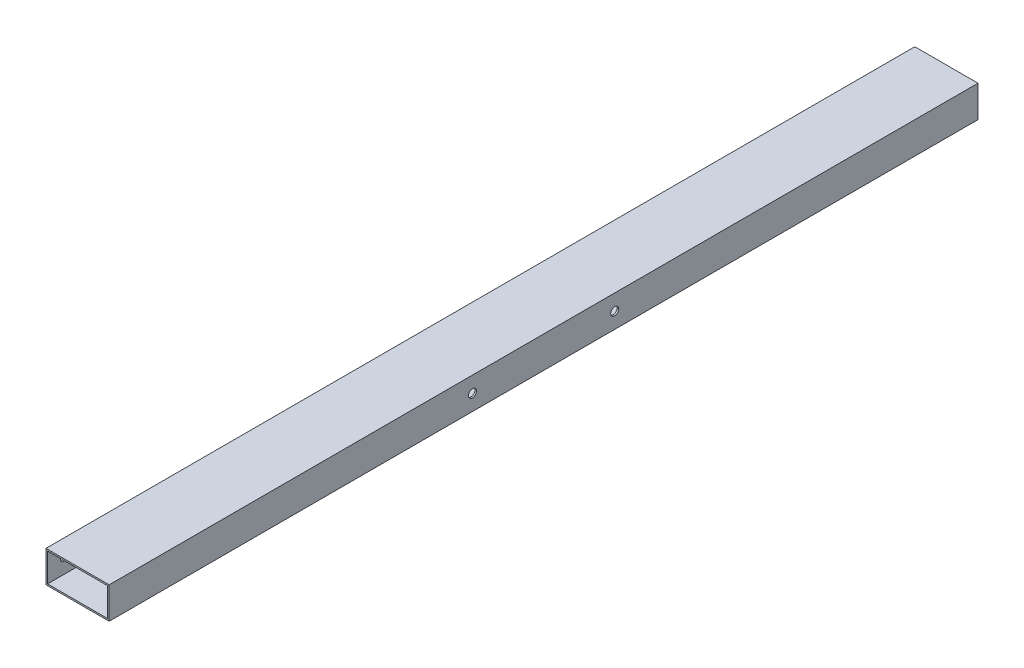
SolidWorks part; units mm, degrees
material "1060 合金"
ref_plane "前视基准面" through (0, 0, 0) normal (0, 0, 1) x (1, 0, 0)
ref_plane "上视基准面" through (0, 0, 0) normal (0, 1, 0) x (1, 0, 0)
ref_plane "右视基准面" through (0, 0, 0) normal (1, 0, 0) x (0, 0, -1)
other "Configuration Table"
sketch "草图1" plane through (0, 0, 0) normal (0, 0, 1) x (1, 0, 0)
  line L1 (0, 0) -> (40, 0)
  line L2 (0, 0) -> (0, -20)
  line L3 (0, -20) -> (40, -20)
  line L4 (40, 0) -> (40, -20)
  dimension "D1" = 20
  dimension "D2" = 40
extrude "拉伸-薄壁1" add sketch "草图1" along normal blind 550 thin
sketch "草图4" plane through (0, 0, 0) normal (-1, 0, 0) x (0, 0, 1)
  line L0 (550, 0) -> (0, 0) construction
  line L1 (550, 0) -> (550, -20) construction
  line L4 (0, -208.7901) -> (0, 661.2099) construction
  circle A1 centre (539.9964, -10) radius 1.75
  circle A49 centre (10, -10) radius 1.75
  dimension "D27" = 3.5
  dimension "D28" = 3.5
  dimension "D29" = 10
  dimension "D25" = 10
  dimension "D26" = 10.0036
  dimension "D30" = 10
extrude "切除-拉伸2" cut sketch "草图4" against normal blind 1.5
sketch "草图5" plane through (0, 0, 0) normal (-1, 0, 0) x (0, 0, 1)
  line L1 (550, 0) -> (0, 0) construction
  line L2 (0, -742.5) -> (0, 127.5) construction
  circle A25 centre (255, -10) radius 2.6
  dimension "D3" = 5.2
  dimension "D1" = 10
  dimension "D2" = 255
extrude "切除-拉伸3" cut sketch "草图5" against normal blind 1.5
sketch "草图6" plane through (40, 0, 0) normal (1, 0, 0) x (0, 0, -1)
  line L0 (-550, -20) -> (0, -20) construction
  line L1 (-550, -20) -> (-550, 0) construction
  line L2 (0, -20) -> (0, 0) construction
  circle A0 centre (-320, -10) radius 2.5
  circle A1 centre (-230, -10) radius 2.5
  dimension "D1" = 5
  dimension "D4" = 5
  dimension "D2" = 10
  dimension "D3" = 230
  dimension "D5" = 10
  dimension "D6" = 230
extrude "切除-拉伸4" cut sketch "草图6" against normal through all
